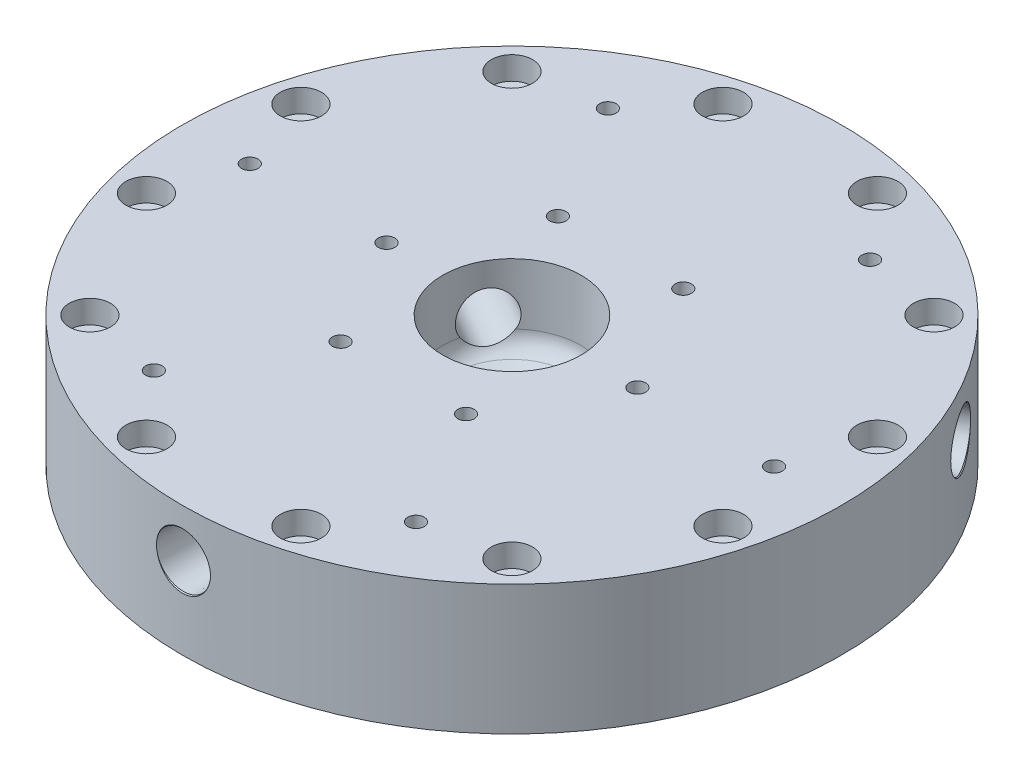
SolidWorks part; units mm, degrees
ref_plane "Front Plane" through (0, 0, 0) normal (0, 0, 1) x (1, 0, 0)
ref_plane "Top Plane" through (0, 0, 0) normal (0, 1, 0) x (1, 0, 0)
ref_plane "Right Plane" through (0, 0, 0) normal (1, 0, 0) x (0, 0, -1)
sketch "Sketch1" plane through (0, 0, 0) normal (0, 1, 0) x (1, 0, 0)
  circle A0 centre (0, 0) radius 76.2
  dimension "D1" = 152.4
extrude "Boss-Extrude1" add sketch "Sketch1" along normal blind 30
sketch "Sketch2" plane through (0, 0, 0) normal (0, 0, 1) x (1, 0, 0)
  line L0 (-5.533, 0) -> (-5.533, 4.1132)
  line L1 (-8.033, 8.4434) -> (-13.5, 11.5997)
  line L2 (-16, 15.9299) -> (-16, 30)
  line L3 (76.2, 30) -> (-76.2, 30) construction
  line L4 (-16, 30) -> (0, 30)
  line L5 (0, 30) -> (0, 0)
  line L6 (0, 0) -> (-5.533, 0)
  line L7 (-76.2, 0) -> (76.2, 0) construction
  arc A0 (-13.5, 11.5997) -> (-16, 15.9299) centre (-11, 15.9299) cw
  arc A1 (-5.533, 4.1132) -> (-8.033, 8.4434) centre (-10.533, 4.1132) ccw
  point P15 (-5.533, 7)
  dimension "D5" = 5
  dimension "D1" = 5.533
  dimension "D2" = 7
  dimension "D3" = 16
  dimension "D4" = 30
revolve "Cut-Revolve1" cut sketch "Sketch2" angle 360 about L5
ref_plane "Plane1" through (0, 0, 76.2) normal (0, 0, 1) x (1, 0, 0)
hole_wizard "1/4 NPT Tapped Hole1" positions "Sketch4" profile "Sketch5" size "1/4" standard "ANSI Inch"
sketch "Sketch4" plane through (0, 0, 76.2) normal (0, 0, 1) x (1, 0, 0)
  point P0 (0, 18.9048)
sketch "Sketch5" plane through (0, 18.9048, 76.2) normal (1, 0, 0) x (0, -1, 0)
  line L0 (0, 0) -> (0, 68.5423)
  line L1 (5.5626, 65.2) -> (0, 68.5423)
  line L2 (-5.5626, 65.2) -> (0, 68.5423) construction
  line L3 (5.5626, 65.2) -> (5.5626, 10.02)
  line L4 (5.5626, 10.02) -> (5.9507, 10.02)
  line L5 (5.9507, 10.02) -> (6.2437, 0.2333)
  line L6 (6.2437, 0.2333) -> (6.477, 0)
  line L7 (6.477, 0) -> (0, 0)
  line L8 (0, -6.35) -> (0, 107.95) construction
  line L9 (-6.2437, 0.2333) -> (-6.477, 0) construction
  line L11 (-5.5626, 10.02) -> (-5.9507, 10.02) construction
  line L12 (-5.9507, 10.02) -> (-6.2437, 0.2333) construction
  dimension "Tap Drill Dia." = 11.1252
  dimension "Tap Drill Depth" = 65.2
  dimension "Thread Dia." = 12.4874
  dimension "Thread Angle" = 3.43
  dimension "Thread Depth" = 10.02
  dimension "C'Sink Dia." = 12.954
  dimension "C'Sink Angle" = 90
  dimension "Drill Angle" = 118
cosmetic thread "Hole Thread1" parameters "D1"=10.02, "D2"=13.716
pattern_circular "CirPattern1" count 3 over 360 about axis through (0, 0, 0) along (0, 1, 0) of "1/4 NPT Tapped Hole1"
cosmetic thread "Hole Thread2" parameters "D1"=10.02, "D2"=13.716
cosmetic thread "Hole Thread3" parameters "D1"=10.02, "D2"=13.716
hole_wizard "CBORE for #10 Socket Head Cap Screw1" positions "Sketch6" profile "Sketch7" counterbore size "#10" standard "ANSI Inch" end condition through all
sketch "Sketch6" plane through (0, 30, 0) normal (0, 1, 0) x (1, 0, 0)
  line L0 (0, 0) -> (0, -69)
  line L2 (0, 0) -> (-17.8585, -66.6489)
  circle A1 centre (0, 0) radius 69
  point P0 (-17.8585, -66.6489)
  point P5 (-17.8585, -66.6489)
  dimension "D2" = 15
sketch "Sketch7" plane through (-17.8585, 30, 66.6489) normal (1, 0, 0) x (0, 0, 1)
  line L0 (0, 0) -> (0, 30)
  line L1 (0, 30) -> (2.4892, 30)
  line L3 (2.4892, 30) -> (2.4892, 5.326)
  line L4 (2.4892, 5.326) -> (4.7625, 5.326)
  line L5 (4.7625, 5.326) -> (4.7625, 0)
  line L7 (4.7625, 0) -> (0, 0)
  line L11 (0, -6.35) -> (0, 107.95) construction
  dimension "Thru Hole Dia." = 4.9784
  dimension "Thru Hole Depth" = 30
  dimension "C'Bore Dia." = 9.525
  dimension "C'Bore Depth" = 5.326
pattern_circular "CirPattern2" count 12 over 360 about axis through (0, 0, 0) along (0, 1, 0) of "CBORE for #10 Socket Head Cap Screw1"
sketch "Sketch12" plane through (0, 30, 0) normal (0, 1, 0) x (1, 0, 0)
  line L0 (0, 0) -> (0, 60.61)
  line L1 (0, 0) -> (30.305, 52.4898)
  circle A0 centre (0, 0) radius 60.61
  dimension "D1" = 121.22
  dimension "D2" = 30
hole_wizard "#10-24 Tapped Hole1" positions "Sketch17" profile "Sketch19" tap size "#10-24" standard "ANSI Inch"
sketch "Sketch17" plane through (0, 30, 0) normal (0, 1, 0) x (1, 0, 0)
  point P0 (30.305, 52.4898)
sketch "Sketch19" plane through (30.305, 30, -52.4898) normal (1, 0, 0) x (0, 0, 1)
  line L0 (0, 0) -> (0, 13.9708)
  line L1 (0, 13.9708) -> (1.8986, 12.83)
  line L2 (1.8986, 12.83) -> (1.8986, 0)
  line L5 (1.8986, 0) -> (0, 0)
  line L10 (0, 13.9708) -> (-1.8987, 12.83) construction
  line L11 (0, -6.35) -> (0, 107.95) construction
  dimension "Tap Drill Dia." = 3.7973
  dimension "Tap Drill Depth" = 12.83
  dimension "Drill Angle" = 118
pattern_circular "CirPattern3" count 6 over 360 about axis through (0, 0, 0) along (0, 1, 0) of "#10-24 Tapped Hole1"
sketch "Sketch20" plane through (0, 0, 0) normal (0, -1, 0) x (-1, 0, 0)
  circle A0 centre (0, 0) radius 55.14
  dimension "D1" = 110.28
sketch "Sketch21" plane through (0, 0, 0) normal (0, 0, 1) x (1, 0, 0)
  line L0 (-76.2, 0) -> (76.2, 0) construction
  line L1 (58.5343, 0) -> (62.5983, 0)
  line L2 (58.5343, 0) -> (58.5343, 2.1844)
  line L3 (59.0423, 2.6924) -> (62.0903, 2.6924)
  line L4 (62.5983, 0) -> (62.5983, 2.1844)
  line L5 (0, 0) -> (0, -8.9782) construction
  arc A0 (58.5343, 2.1844) -> (59.0423, 2.6924) centre (59.0423, 2.1844) cw
  arc A1 (62.0903, 2.6924) -> (62.5983, 2.1844) centre (62.0903, 2.1844) cw
  point P11 (58.5343, 2.6924)
  point P14 (62.5983, 2.6924)
  dimension "D4" = 0.508
  dimension "D1" = 58.5343
  dimension "D2" = 4.064
  dimension "D3" = 2.6924
revolve "Cut-Revolve2" cut sketch "Sketch21" angle 360 about L5
hole_wizard "#21 (0.159) Diameter Hole1" positions "Sketch27" profile "Sketch28" tap size "#10-24" standard "ANSI Inch"
sketch "Sketch27" plane through (0, 30, 0) normal (0, 1, 0) x (1, 0, 0)
  point P0 (29, 0)
  dimension "D1" = 29
sketch "Sketch28" plane through (29, 30, 0) normal (1, 0, 0) x (0, 0, 1)
  line L0 (0, 0) -> (0, 19.1408)
  line L1 (0, 19.1408) -> (1.8986, 18)
  line L2 (1.8986, 18) -> (1.8986, 0)
  line L5 (1.8986, 0) -> (0, 0)
  line L10 (0, 19.1408) -> (-1.8987, 18) construction
  line L11 (0, -6.35) -> (0, 107.95) construction
  dimension "Tap Drill Dia." = 3.7973
  dimension "Tap Drill Depth" = 18
  dimension "Drill Angle" = 118
pattern_circular "CirPattern4" count 6 over 360 about axis through (0, 0, 0) along (0, 1, 0) of "#21 (0.159) Diameter Hole1"
sketch "Sketch29" plane through (0, 0, 0) normal (0, -1, 0) x (-1, 0, 0)
  circle A0 centre (0, 0) radius 55.14
  circle A1 centre (0, 0) radius 5.533
  dimension "D1" = 110.28
  dimension "D2" = 11.066
extrude "Boss-Extrude2" add sketch "Sketch29" along normal blind 2
fillet "Fillet1" radius 0.127 2 edges at (0, 0, 58.5343) (0, 0, 62.5983)
chamfer "Chamfer1" distance 0.3 angle 45 1 edges at (0, -2, -55.14)
